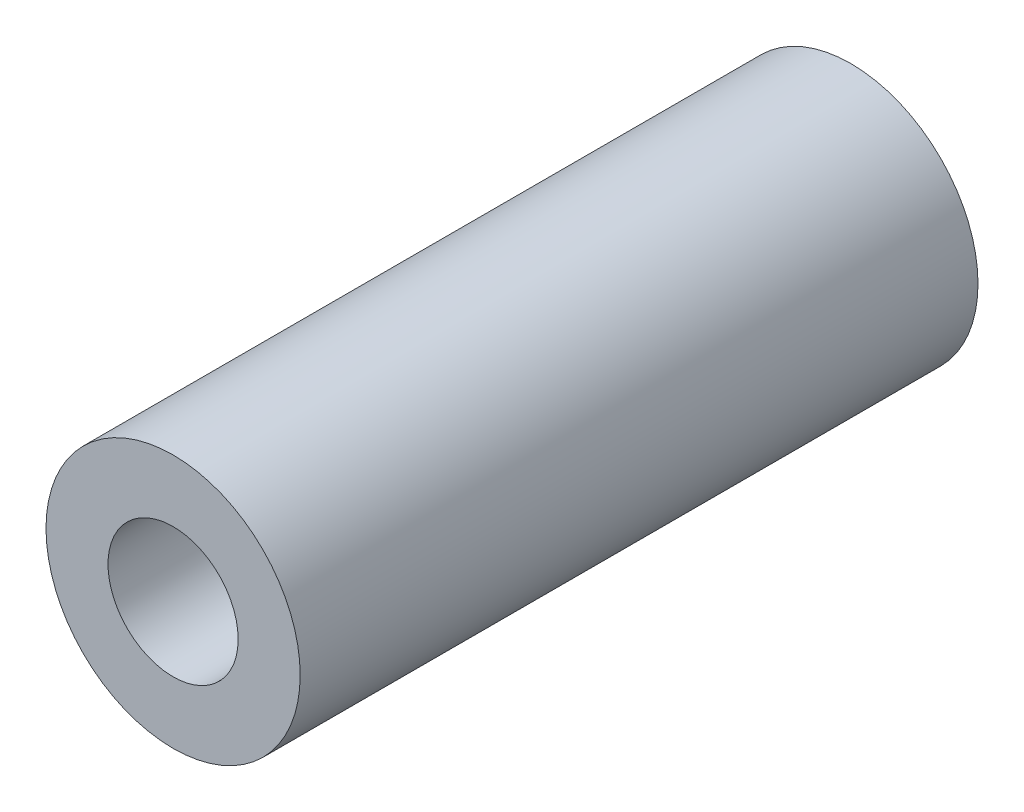
SolidWorks part; units mm, degrees
material "6061-T6 (SS)"
ref_plane "Front Plane" through (0, 0, 0) normal (0, 0, 1) x (1, 0, 0)
ref_plane "Top Plane" through (0, 0, 0) normal (0, 1, 0) x (1, 0, 0)
ref_plane "Right Plane" through (0, 0, 0) normal (1, 0, 0) x (0, 0, -1)
sketch "Sketch1" plane through (0, 0, 0) normal (1, 0, 0) x (0, 0, -1)
  line L0 (-43.4652, 0) -> (107.0331, 0) construction
  line L1 (0, 0) -> (0, 2.4384) construction
  line L2 (-12.7, 4.7625) -> (12.7, 4.7625)
  line L3 (-12.7, 4.7625) -> (-12.7, 2.4384)
  line L4 (-12.7, 2.4384) -> (12.7, 2.4384)
  line L5 (12.7, 4.7625) -> (12.7, 2.4384)
  dimension "ID" = 4.8768
  dimension "OD" = 9.525
  dimension "L" = 25.4
revolve "Revolve1" add sketch "Sketch1" angle 360 about L0
